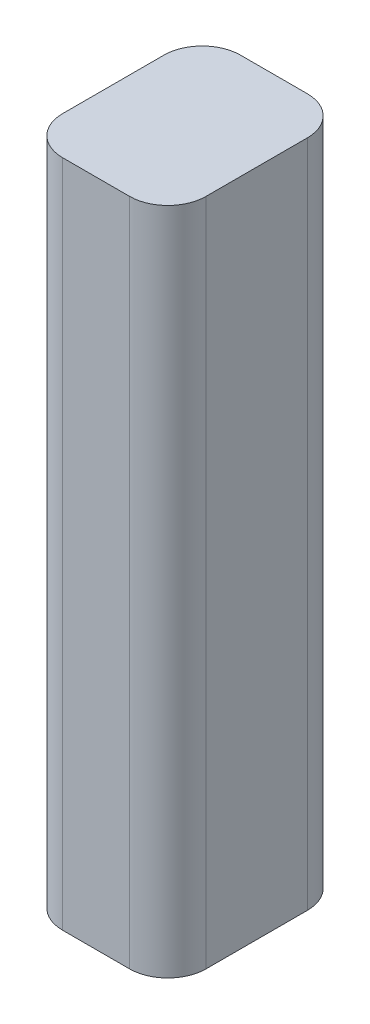
SolidWorks part; units mm, degrees
material "PLA"
ref_plane "Front Plane" through (0, 0, 0) normal (0, 0, 1) x (1, 0, 0)
ref_plane "Top Plane" through (0, 0, 0) normal (0, 1, 0) x (1, 0, 0)
ref_plane "Right Plane" through (0, 0, 0) normal (1, 0, 0) x (0, 0, -1)
sketch "Sketch1" plane through (0, 0, 0) normal (0, 1, 0) x (1, 0, 0)
  line L0 (-3.75, -2.65) -> (-3.75, 2.65)
  line L1 (-1.75, 4.65) -> (1.75, 4.65)
  line L2 (3.75, 2.65) -> (3.75, -2.65)
  line L3 (1.75, -4.65) -> (-1.75, -4.65)
  arc A0 (-3.75, 2.65) -> (-1.75, 4.65) centre (-1.75, 2.65) cw
  arc A1 (1.75, 4.65) -> (3.75, 2.65) centre (1.75, 2.65) cw
  arc A2 (3.75, -2.65) -> (1.75, -4.65) centre (1.75, -2.65) cw
  arc A3 (-1.75, -4.65) -> (-3.75, -2.65) centre (-1.75, -2.65) cw
  point P12 (0, 4.65)
  point P14 (3.75, 0)
  dimension "D3" = 2
  dimension "D1" = 7.5
  dimension "D2" = 9.3
extrude "Boss-Extrude1" add sketch "Sketch1" along normal mid plane 35
